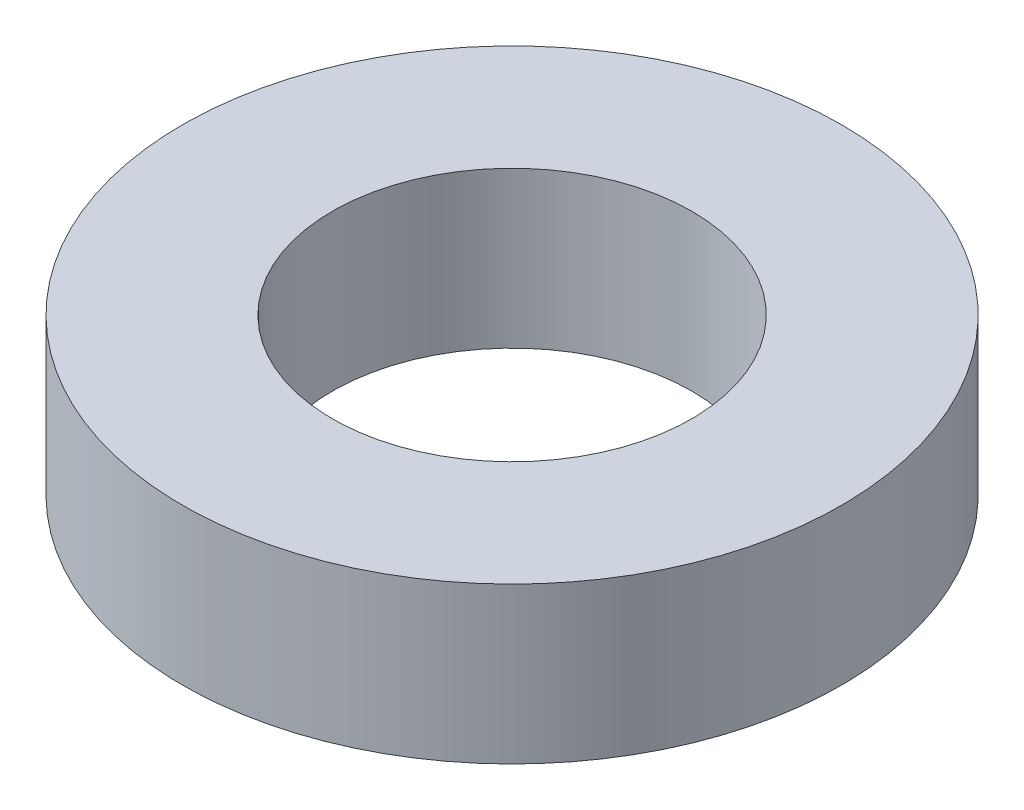
SolidWorks part; units mm, degrees
ref_plane "Front Plane" through (0, 0, 0) normal (0, 0, 1) x (1, 0, 0)
ref_plane "Top Plane" through (0, 0, 0) normal (0, 1, 0) x (1, 0, 0)
ref_plane "Right Plane" through (0, 0, 0) normal (1, 0, 0) x (0, 0, -1)
sketch "Sketch1" plane through (0, 0, 0) normal (0, 1, 0) x (1, 0, 0)
  circle A0 centre (0, 0) radius 27.5
  circle A1 centre (0, 0) radius 15
  dimension "D1" = 55
  dimension "D2" = 30
extrude "Boss-Extrude1" add sketch "Sketch1" along normal blind 13
